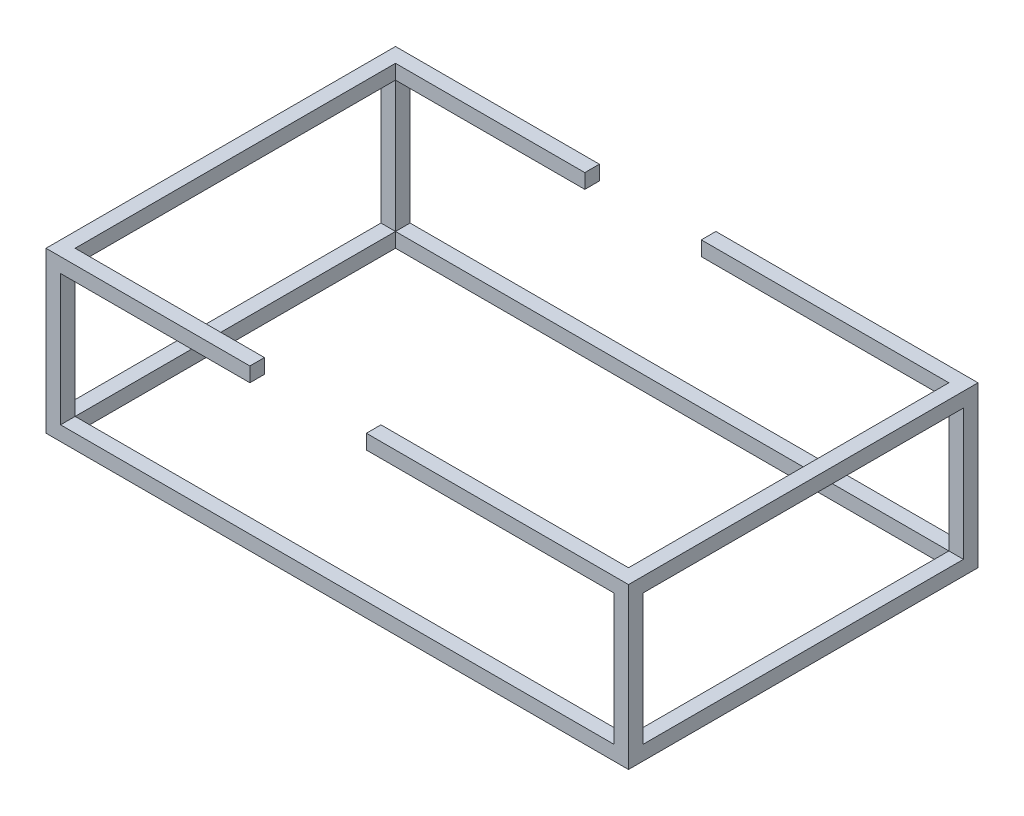
SolidWorks part; units mm, degrees
material "Stainless Steel (ferritic)"
ref_plane "Front Plane" through (0, 0, 0) normal (0, 0, 1) x (1, 0, 0)
ref_plane "Top Plane" through (0, 0, 0) normal (0, 1, 0) x (1, 0, 0)
ref_plane "Right Plane" through (0, 0, 0) normal (1, 0, 0) x (0, 0, -1)
sketch "Sketch3" plane through (0, 0, 0) normal (0, 1, 0) x (1, 0, 0)
  line L0 (-482.6, 279.4) -> (482.6, 279.4)
  line L1 (-508, -304.8) -> (508, -304.8)
  line L2 (-508, -304.8) -> (-508, 304.8)
  line L3 (-508, 304.8) -> (508, 304.8)
  line L4 (508, -304.8) -> (508, 304.8)
  line L5 (-508, -304.8) -> (508, 304.8) construction
  line L6 (-508, 304.8) -> (508, -304.8) construction
  line L7 (482.6, -279.4) -> (482.6, 279.4)
  line L8 (-482.6, -279.4) -> (482.6, -279.4)
  line L9 (-482.6, -279.4) -> (-482.6, 279.4)
  point P0 (0, 0)
  dimension "D1" = 609.6
  dimension "D2" = 1016
  dimension "D3" = 25.4
extrude "Boss-Extrude1" add sketch "Sketch3" along normal blind 25.4
sketch "Sketch4" plane through (0, 25.4, 0) normal (0, 1, 0) x (1, 0, 0)
  line L1 (-508, 304.8) -> (-482.6, 304.8)
  line L2 (-508, 304.8) -> (-508, 279.4)
  line L3 (-508, 279.4) -> (-482.6, 279.4)
  line L4 (-482.6, 304.8) -> (-482.6, 279.4)
  line L5 (508, 304.8) -> (482.6, 304.8)
  line L6 (508, 304.8) -> (508, 279.4)
  line L7 (508, 279.4) -> (482.6, 279.4)
  line L8 (482.6, 304.8) -> (482.6, 279.4)
  line L9 (482.6, -279.4) -> (508, -279.4)
  line L10 (482.6, -279.4) -> (482.6, -304.8)
  line L11 (482.6, -304.8) -> (508, -304.8)
  line L12 (508, -279.4) -> (508, -304.8)
  line L13 (-482.6, -279.4) -> (-508, -279.4)
  line L14 (-482.6, -279.4) -> (-482.6, -304.8)
  line L15 (-482.6, -304.8) -> (-508, -304.8)
  line L16 (-508, -279.4) -> (-508, -304.8)
extrude "Boss-Extrude2" add sketch "Sketch4" along normal blind 228.6
sketch "Sketch6" plane through (-482.6, 0, 0) normal (1, 0, 0) x (0, 0, -1)
  line L1 (-279.4, 254) -> (-304.8, 254)
  line L2 (-279.4, 254) -> (-279.4, 279.4)
  line L3 (-279.4, 279.4) -> (-304.8, 279.4)
  line L4 (-304.8, 254) -> (-304.8, 279.4)
  line L5 (304.8, 254) -> (279.4, 254)
  line L6 (304.8, 254) -> (304.8, 279.4)
  line L7 (304.8, 279.4) -> (279.4, 279.4)
  line L8 (279.4, 254) -> (279.4, 279.4)
  dimension "D1" = 25.4
  dimension "D2" = 25.4
  dimension "D3" = 25.4
  dimension "D4" = 25.4
extrude "Boss-Extrude3" add sketch "Sketch6" along normal blind 330.2 and the other way blind 25.4
sketch "Sketch7" plane through (482.6, 0, 0) normal (-1, 0, 0) x (0, 0, 1)
  line L1 (279.4, 254) -> (304.8, 254)
  line L2 (279.4, 254) -> (279.4, 279.4)
  line L3 (279.4, 279.4) -> (304.8, 279.4)
  line L4 (304.8, 254) -> (304.8, 279.4)
  line L5 (-304.8, 254) -> (-279.4, 254)
  line L6 (-304.8, 254) -> (-304.8, 279.4)
  line L7 (-304.8, 279.4) -> (-279.4, 279.4)
  line L8 (-279.4, 254) -> (-279.4, 279.4)
  dimension "D1" = 25.4
  dimension "D2" = 25.4
  dimension "D3" = 25.4
  dimension "D4" = 25.4
extrude "Boss-Extrude4" add sketch "Sketch7" along normal blind 431.8 and the other way blind 25.4
sketch "Sketch8" plane through (0, 0, -279.4) normal (0, 0, 1) x (1, 0, 0)
  line L1 (508, 279.4) -> (482.6, 279.4)
  line L2 (508, 279.4) -> (508, 254)
  line L3 (508, 254) -> (482.6, 254)
  line L4 (482.6, 279.4) -> (482.6, 254)
  line L5 (-482.6, 254) -> (-508, 254)
  line L6 (-482.6, 254) -> (-482.6, 279.4)
  line L7 (-482.6, 279.4) -> (-508, 279.4)
  line L8 (-508, 254) -> (-508, 279.4)
extrude "Boss-Extrude5" add sketch "Sketch8" along normal blind 558.8
